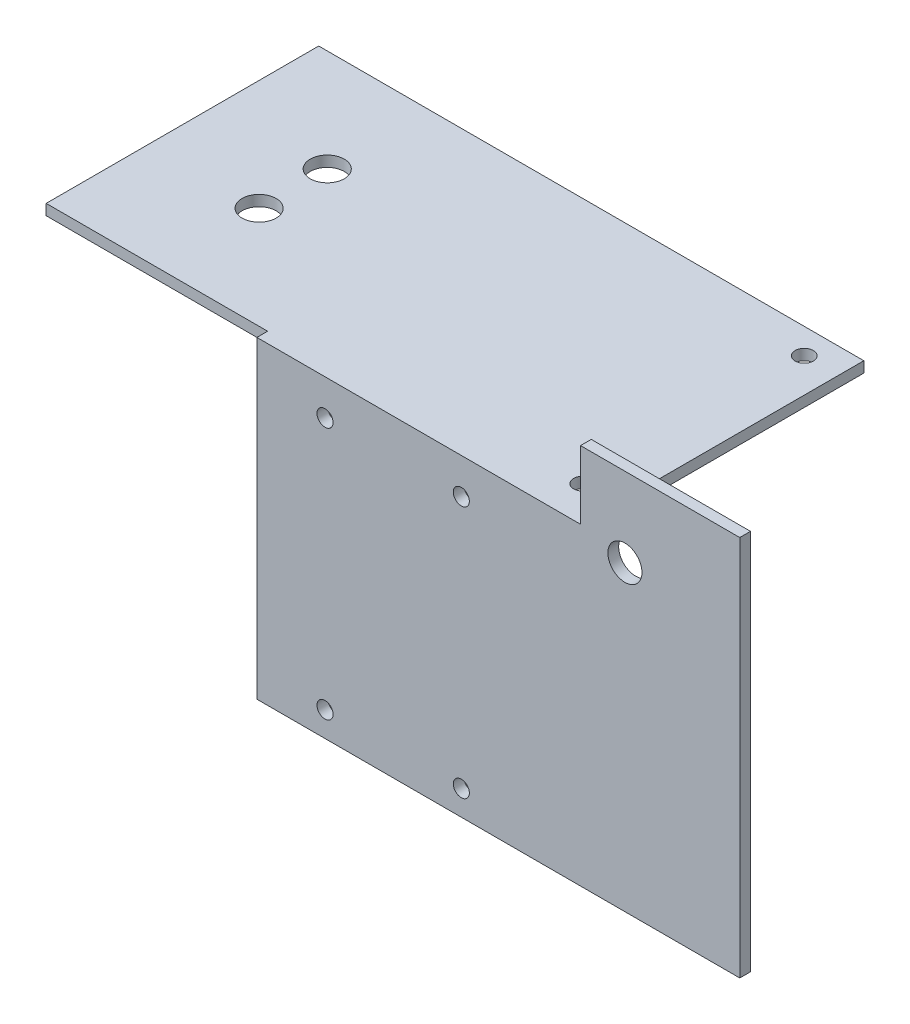
SolidWorks part; units mm, degrees
material "Galvanized Steel"
ref_plane "Front Plane" through (0, 0, 0) normal (0, 0, 1) x (1, 0, 0)
ref_plane "Top Plane" through (0, 0, 0) normal (0, 1, 0) x (1, 0, 0)
ref_plane "Right Plane" through (0, 0, 0) normal (1, 0, 0) x (0, 0, -1)
sketch "Sketch1" plane through (0, 0, 0) normal (0, 0, 1) x (1, 0, 0)
  line L0 (38.1, 51.75) -> (12.7, 51.75) construction
  line L1 (0, 58.4) -> (60.325, 58.4)
  line L2 (0, 58.4) -> (0, 0)
  line L3 (0, 0) -> (90, 0)
  line L4 (60.325, 58.4) -> (60.325, 71.1)
  line L5 (60.325, 71.1) -> (90, 71.1)
  line L6 (12.7, 51.75) -> (12.7, 4.65) construction
  line L7 (90, 71.1) -> (90, 0)
  line L8 (12.7, 4.65) -> (38.1, 4.65) construction
  line L9 (38.1, 51.75) -> (38.1, 4.65) construction
  circle A0 centre (68.6, 56.332) radius 3.175
  circle A4 centre (12.7, 51.75) radius 1.5
  circle A5 centre (38.1, 51.75) radius 1.5
  circle A6 centre (12.7, 4.65) radius 1.5
  circle A7 centre (38.1, 4.65) radius 1.5
  dimension "D3" = 3
  dimension "D10" = 21.4
  dimension "D11" = 6.35
  dimension "D1" = 58.4
  dimension "D2" = 90
  dimension "D4" = 47.1
  dimension "D5" = 60.325
  dimension "D6" = 4.65
  dimension "D7" = 25.4
  dimension "D8" = 12.7
  dimension "D9" = 12.7
  dimension "D12" = 2.068
extrude "Boss-Extrude1" add sketch "Sketch1" against normal blind 2
sketch "Sketch2" plane through (0, 0, -2) normal (0, 0, -1) x (-1, 0, 0)
  line L0 (0, 56.4) -> (41.275, 56.4)
  line L1 (0, 58.4) -> (0, 0) construction
  line L2 (0, 56.4) -> (-60.325, 56.4)
  line L3 (-60.325, 56.4) -> (-60.325, 58.4)
  line L5 (-60.325, 58.4) -> (0, 58.4)
  line L6 (41.275, 56.4) -> (41.275, 58.4)
  line L7 (41.275, 58.4) -> (0, 58.4)
  dimension "D1" = 60.325
  dimension "D2" = 41.275
  dimension "D3" = 2
extrude "Boss-Extrude2" add sketch "Sketch2" along normal blind 50.8
sketch "Sketch3" plane through (0, 58.4, 0) normal (0, 1, 0) x (1, 0, 0)
  line L0 (53.975, 48.0375) -> (53.975, 6.7625) construction
  line L1 (-41.275, 52.8) -> (60.325, 52.8) construction
  line L2 (60.325, 52.8) -> (60.325, 2) construction
  line L3 (-20.6375, 33.75) -> (-20.6375, 21.05) construction
  line L4 (-41.275, 52.8) -> (-41.275, 2) construction
  circle A0 centre (53.975, 48.0375) radius 1.7
  circle A1 centre (53.975, 6.7625) radius 1.7
  circle A2 centre (-20.6375, 33.75) radius 3.175
  circle A3 centre (-20.6375, 21.05) radius 3.175
  point P10 (-20.6375, 27.4)
  point P13 (-41.275, 27.4)
  dimension "D1" = 3.4
  dimension "D2" = 41.275
  dimension "D6" = 6.35
  dimension "D7" = 6.35
  dimension "D3" = 4.7625
  dimension "D4" = 6.35
  dimension "D5" = 12.7
  dimension "D8" = 20.6375
extrude "Cut-Extrude1" cut sketch "Sketch3" against normal through all
